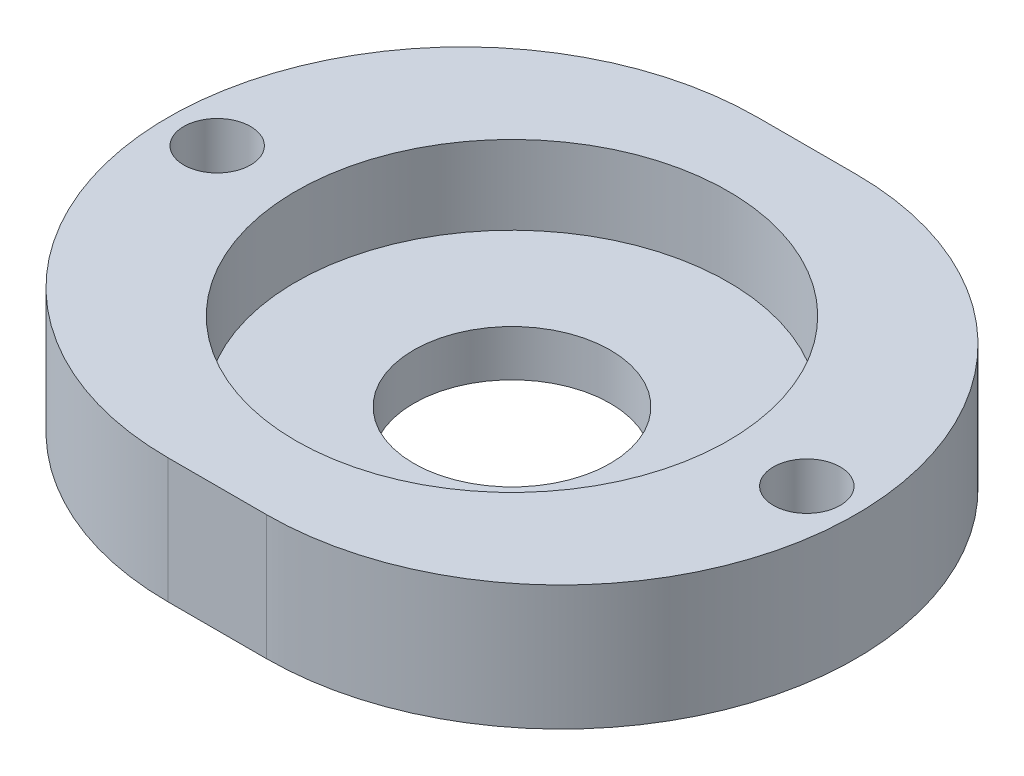
SolidWorks part; units mm, degrees
ref_plane "Front Plane" through (0, 0, 0) normal (0, 0, 1) x (1, 0, 0)
ref_plane "Top Plane" through (0, 0, 0) normal (0, 1, 0) x (1, 0, 0)
ref_plane "Right Plane" through (0, 0, 0) normal (1, 0, 0) x (0, 0, -1)
sketch "Sketch3" plane through (0, 0, 0) normal (0, 1, 0) x (1, 0, 0)
  line L0 (0, 15) -> (5, 15) construction
  line L1 (0, 0) -> (5, 0)
  line L2 (2.5, 30) -> (2.5, 0) construction
  line L3 (0, 30) -> (5, 30)
  arc A0 (0, 30) -> (0, 0) centre (0, 15) ccw
  arc A1 (5, 0) -> (5, 30) centre (5, 15) ccw
  circle A2 centre (2.5, 15) radius 5
  dimension "D1" = 10
  dimension "D2" = 5
  dimension "D3" = 30
extrude "Boss-Extrude1" add sketch "Sketch3" along normal blind 6.35
sketch "Sketch4" plane through (0, 6.35, 0) normal (0, 1, 0) x (1, 0, 0)
  circle A0 centre (2.5, 15) radius 11
  dimension "D1" = 22
extrude "Cut-Extrude1" cut sketch "Sketch4" against normal blind 4
hole_wizard "M3 Clearance Hole1" positions "3DSketch1" profile "Sketch6" hole size "M3" standard "ANSI Metric" end condition through all
sketch3d "3DSketch1"
  line L10 (2.5, 6.35, -15) -> (17.5, 6.35, -15) construction
  line L11 (2.5, 2.35, -15) -> (2.5, 6.35, -15) construction
  line L12 (2.5, 6.35, -15) -> (-12.5, 6.35, -15) construction
  point P13 (-12.5, 6.35, -15)
  point P23 (17.5, 6.35, -15)
  dimension "D1" = 30
sketch "Sketch6" plane through (-12.5, 6.35, -15) normal (1, 0, 0) x (0, 0, 1)
  line L0 (0, 0) -> (0, 6.35)
  line L1 (0, 6.35) -> (1.7, 6.35)
  line L2 (1.7, 6.35) -> (1.7, 0)
  line L5 (1.7, 0) -> (0, 0)
  line L11 (0, -6.35) -> (0, 107.95) construction
  dimension "Thru Hole Dia." = 3.4
  dimension "Thru Hole Depth" = 6.35
